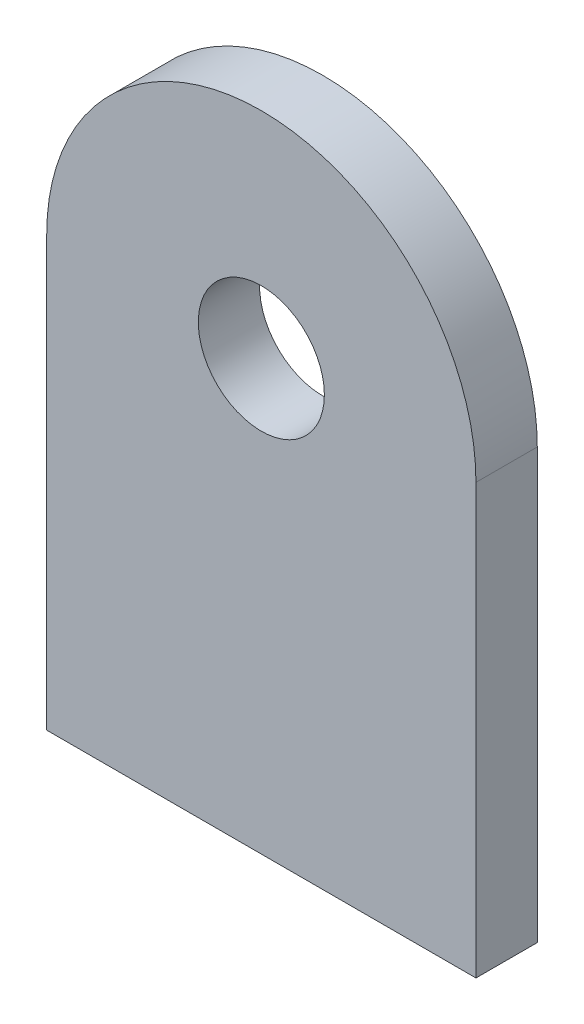
SolidWorks part; units mm, degrees
material "1023 Carbon Steel Sheet (SS)"
ref_plane "Front Plane" through (0, 0, 0) normal (0, 0, 1) x (1, 0, 0)
ref_plane "Top Plane" through (0, 0, 0) normal (0, 1, 0) x (1, 0, 0)
ref_plane "Right Plane" through (0, 0, 0) normal (1, 0, 0) x (0, 0, -1)
sketch "Sketch1" plane through (0, 0, 0) normal (0, 0, 1) x (1, 0, 0)
  line L0 (0, 0) -> (22.225, 0)
  line L1 (22.225, 0) -> (22.225, 22.225)
  line L2 (0, 22.225) -> (0, 0)
  line L3 (11.1125, 22.225) -> (11.1125, 0) construction
  arc A0 (22.225, 22.225) -> (0, 22.225) centre (11.1125, 22.225) ccw
  circle A1 centre (11.1125, 22.225) radius 3.2639
  dimension "D2" = 6.5278
  dimension "D3" = 22.225
  dimension "D4" = 22.225
  dimension "D5" = 11.1125
  dimension "D1" = 22.225
extrude "Boss-Extrude1" add sketch "Sketch1" along normal blind 3.175
